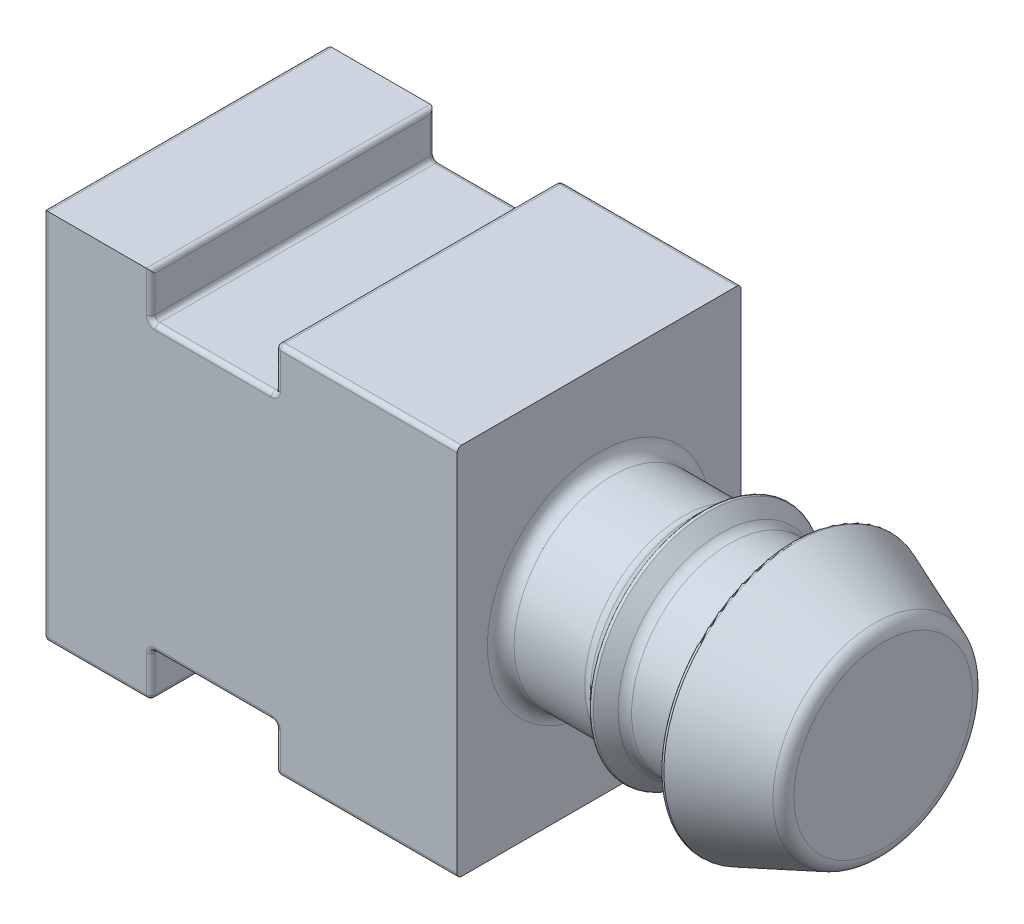
SolidWorks part; units mm, degrees
ref_plane "Front Plane" through (0, 0, 0) normal (0, 0, 1) x (1, 0, 0)
ref_plane "Top Plane" through (0, 0, 0) normal (0, 1, 0) x (1, 0, 0)
ref_plane "Right Plane" through (0, 0, 0) normal (1, 0, 0) x (0, 0, -1)
sketch "Sketch2" plane through (0, 0, 0) normal (0, 1, 0) x (1, 0, 0)
  line L0 (0, -6.35) -> (0, 6.35)
  line L1 (0, 6.35) -> (-18.5, 6.35)
  line L2 (-18.5, 6.35) -> (-18.5, -6.35)
  line L3 (-18.5, -6.35) -> (0, -6.35)
  circle A0 centre (-12.7, 0) radius 3.175
  point P4 (0, 0)
  point P10 (-18.5, 0)
  dimension "D3" = 6.35
  dimension "D4" = 5.8
  dimension "D1" = 12.7
  dimension "D2" = 12.7
extrude "Boss-Extrude2" add sketch "Sketch2" along normal mid plane 12.7
sketch "Sketch3" plane through (0, 0, 0) normal (0, 0, 1) x (1, 0, 0)
  line L1 (0, 6.35) -> (0, -6.35) construction
  line L4 (0, 0) -> (0, 4.4)
  line L13 (12.7, 4.4) -> (12.7, 0)
  line L14 (12.7, 0) -> (0, 0)
  line L15 (12.7, 4.4) -> (8.7, 6)
  line L16 (8.7, 6) -> (8.7, 4.4)
  line L23 (0, 4.4) -> (4, 4.4)
  line L25 (5.6, 4.4) -> (4.8, 5.2)
  line L26 (4.8, 5.2) -> (4, 4.4)
  line L27 (5.6, 4.4) -> (8.7, 4.4)
  line L29 (4.8, 5.2) -> (4.8, 4.4) construction
  line L30 (5.6, 4.4) -> (4.8, 4.4) construction
  point P14 (4.8, 4.4)
  dimension "D1" = 12.7
  dimension "D2" = 4.4
  dimension "D3" = 4
  dimension "D4" = 1.6
  dimension "D5" = 7.9
  dimension "D6" = 0.8
revolve "Revolve1" add sketch "Sketch3" angle 360 about L14
sketch "Sketch18" plane through (12.7, 0, 0) normal (1, 0, 0) x (0, 0, -1)
  circle A0 centre (0, 0) radius 2.4
  dimension "D1" = 4.8
sketch "Sketch12" plane through (0, -6.35, 0) normal (0, -1, 0) x (1, 0, 0)
  circle A0 centre (-12.7, 0) radius 3.175
extrude "Boss-Extrude3" add sketch "Sketch12" against normal blind 12.7
sketch "Sketch13" plane through (0, -6.35, 0) normal (0, -1, 0) x (1, 0, 0)
  line L1 (0, 6.35) -> (-18.5, 6.35)
  line L2 (0, 6.35) -> (0, -6.35)
  line L3 (0, -6.35) -> (-18.5, -6.35)
  line L4 (-18.5, 6.35) -> (-18.5, -6.35)
extrude "Boss-Extrude4" add sketch "Sketch13" along normal blind 2
mirror "Mirror1" about plane through (0, 0, 0) normal (0, 1, 0) of "Boss-Extrude4"
sketch "Sketch15" plane through (0, 0, -6.35) normal (0, 0, -1) x (-1, 0, 0)
  line L1 (8.1, 8.35) -> (13.7, 8.35)
  line L2 (8.1, 8.35) -> (8.1, 6.35)
  line L3 (8.1, 6.35) -> (13.7, 6.35)
  line L4 (13.7, 8.35) -> (13.7, 6.35)
  line L5 (18.5, 8.35) -> (0, 8.35) construction
  line L10 (18.5, 8.35) -> (18.5, -8.35) construction
  line L11 (0, 0) -> (50000, 0) construction
  line L12 (13.7, -8.35) -> (13.7, -6.35)
  line L13 (8.1, -6.35) -> (13.7, -6.35)
  line L14 (8.1, -8.35) -> (8.1, -6.35)
  line L15 (8.1, -8.35) -> (13.7, -8.35)
  point P8 (18.5, 0)
  point P14 (8.1, 7.35)
  dimension "D1" = 2
  dimension "D3" = 4.8
  dimension "D4" = 5.6
extrude "Cut-Extrude1" cut sketch "Sketch15" against normal through all
fillet "Fillet1" radius 0.1 2 edges at (4.8, 5.2, 0) (8.7, 6, 0)
fillet "Fillet2" radius 0.6 5 edges at (8.7, 4.4, 0) (5.6, 4.4, 0) (4, 4.4, 0) (0, 4.4, 0) (12.7, 4.4, 0)
fillet "Fillet5" radius 0.2 28 edges at (-4.05, -8.35, 6.35) (-18.5, -8.35, 0) (-16.1, -8.35, -6.35) (-18.5, 8.35, 0) (-16.1, -8.35, 6.35) (-4.05, -8.35, -6.35) (-8.1, 7.35, 6.35) (-8.1, 6.35, 0) (-8.1, 8.35, 0) (-13.7, 7.35, 6.35) (-13.7, 8.35, 0) (-10.9, 6.35, 6.35) (-13.7, 6.35, 0) (-8.1, 7.35, -6.35) (-10.9, 6.35, -6.35) (-13.7, 7.35, -6.35) (-13.7, -8.35, 0) (-8.1, -7.35, 6.35) (-8.1, -8.35, 0) (-10.9, -6.35, 6.35) (-8.1, -6.35, 0) (-13.7, -7.35, 6.35) (-13.7, -6.35, 0) (-13.7, -7.35, -6.35) (-10.9, -6.35, -6.35) (-8.1, -7.35, -6.35) (-18.5, 0, 6.35) (-18.5, 0, -6.35)
